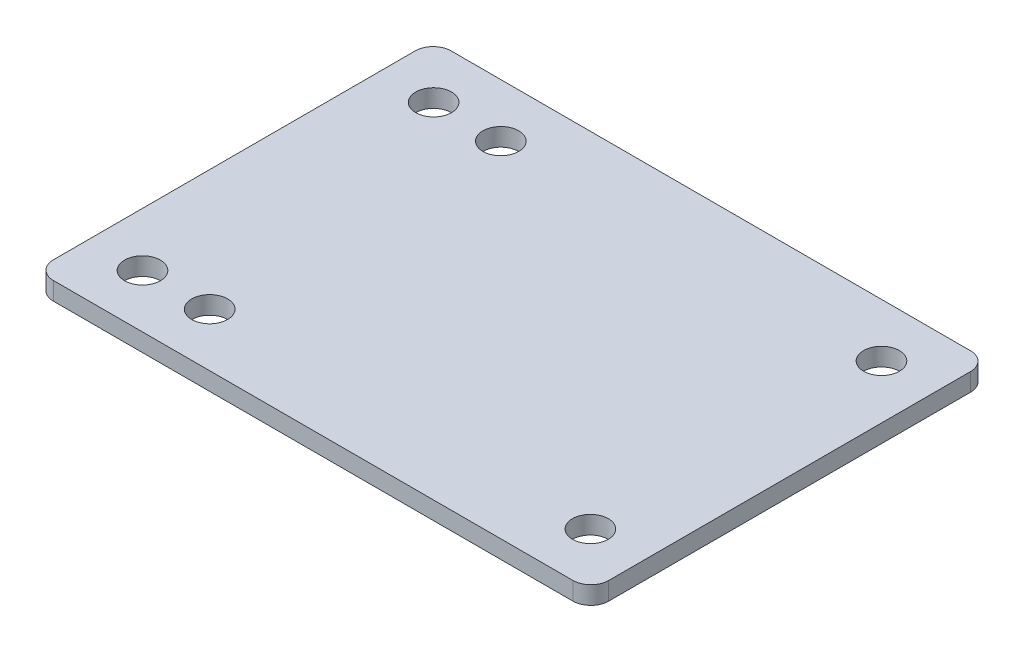
SolidWorks part; units mm, degrees
ref_plane "Front Plane" through (0, 0, 0) normal (0, 0, 1) x (1, 0, 0)
ref_plane "Top Plane" through (0, 0, 0) normal (0, 1, 0) x (1, 0, 0)
ref_plane "Right Plane" through (0, 0, 0) normal (1, 0, 0) x (0, 0, -1)
sketch "Sketch1" plane through (0, 0, 0) normal (0, 1, 0) x (1, 0, 0)
  line L1 (-39.37, -28.194) -> (39.37, -28.194)
  line L2 (-39.37, -28.194) -> (-39.37, 28.194)
  line L3 (-39.37, 28.194) -> (39.37, 28.194)
  line L4 (39.37, -28.194) -> (39.37, 28.194)
  line L5 (-39.37, -28.194) -> (39.37, 28.194) construction
  line L6 (-39.37, 28.194) -> (39.37, -28.194) construction
  point P0 (0, 0)
  dimension "D1" = 78.74
  dimension "D2" = 56.388
extrude "Boss-Extrude1" add sketch "Sketch1" along normal blind 2.54
fillet "Fillet1" radius 2.54 4 edges at (39.37, 1.27, -28.194) (39.37, 1.27, 28.194) (-39.37, 1.27, -28.194) (-39.37, 1.27, 28.194)
sketch "Sketch2" plane through (0, 2.54, 0) normal (0, 1, 0) x (1, 0, 0)
  line L1 (31.75, -20.6375) -> (-31.75, -20.6375)
  line L2 (31.75, -20.6375) -> (31.75, 20.6375)
  line L3 (31.75, 20.6375) -> (-31.75, 20.6375)
  line L4 (-31.75, -20.6375) -> (-31.75, 20.6375)
  line L5 (31.75, -20.6375) -> (-31.75, 20.6375) construction
  line L6 (31.75, 20.6375) -> (-31.75, -20.6375) construction
  circle A0 centre (31.75, 20.6375) radius 2.54
  circle A1 centre (31.75, -20.6375) radius 2.54
  circle A2 centre (-31.75, -20.6375) radius 2.54
  circle A3 centre (-31.75, 20.6375) radius 2.54
  circle A4 centre (-22.225, -20.6375) radius 2.54
  circle A5 centre (-22.225, 20.6375) radius 2.54
  point P0 (0, 0)
  dimension "D3" = 53.975
  dimension "D4" = 53.975
  dimension "D1" = 63.5
  dimension "D2" = 41.275
extrude "Cut-Extrude1" cut sketch "Sketch2" against normal blind 2.54 contours A2 | A4 | A3 | A5 | A1 | A0
